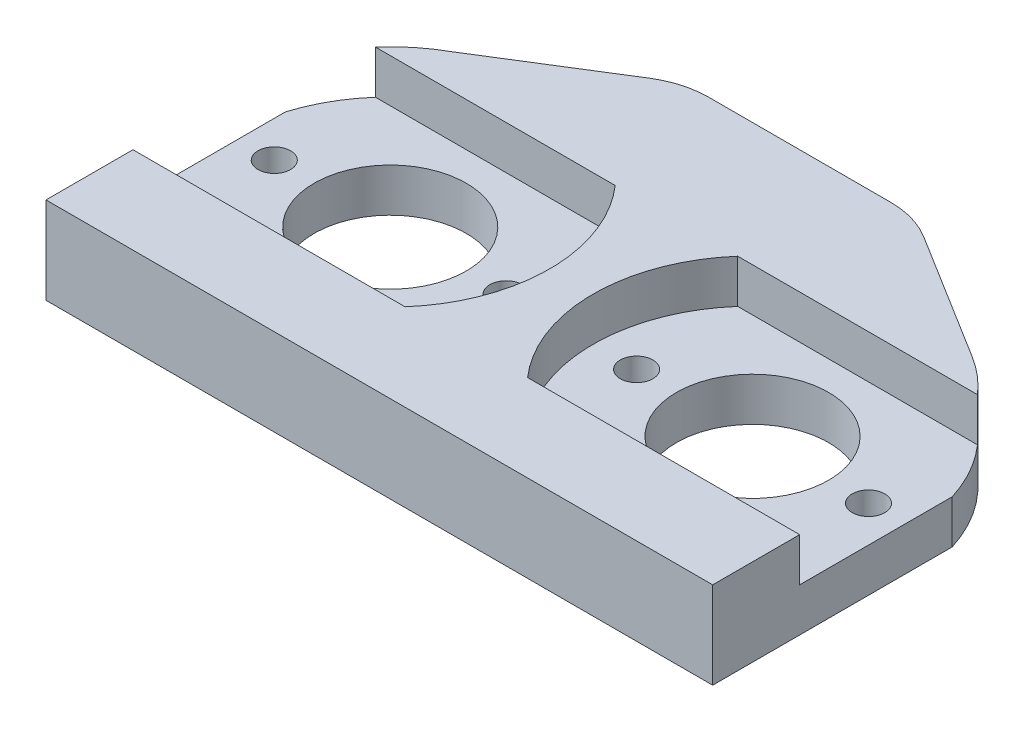
SolidWorks part; units mm, degrees
material "Beech"
ref_plane "Front Plane" through (0, 0, 0) normal (0, 0, 1) x (1, 0, 0)
ref_plane "Top Plane" through (0, 0, 0) normal (0, 1, 0) x (1, 0, 0)
ref_plane "Right Plane" through (0, 0, 0) normal (1, 0, 0) x (0, 0, -1)
sketch "Sketch1" plane through (0, 0, 0) normal (0, 1, 0) x (1, 0, 0)
  line L1 (-46, 28) -> (46, 28)
  line L2 (-46, 28) -> (-46, -28)
  line L3 (-46, -28) -> (46, -28)
  line L4 (46, 28) -> (46, -28)
  line L5 (-46, 28) -> (46, -28) construction
  line L6 (-46, -28) -> (46, 28) construction
  point P0 (0, 0)
  dimension "D1" = 56
  dimension "D2" = 92
extrude "Boss-Extrude1" add sketch "Sketch1" along normal blind 12
sketch "Sketch8" plane through (0, 12, 0) normal (0, 1, 0) x (1, 0, 0)
  line L1 (-46, 28) -> (46, 28)
  line L2 (-46, 28) -> (-46, 30)
  line L3 (-46, 30) -> (46, 30)
  line L4 (46, 28) -> (46, 30)
  dimension "D1" = 2
extrude "Boss-Extrude3" add sketch "Sketch8" against normal blind 12
sketch "Sketch2" plane through (0, 12, 0) normal (0, 1, 0) x (1, 0, 0)
  line L0 (-55.7629, -1.5) -> (57.1831, -1.5) construction
  line L1 (-46, -28) -> (46, -28) construction
  circle A0 centre (-25, -1.5) radius 10.5
  circle A1 centre (25, -1.5) radius 10.5
  point P6 (0, -28)
  dimension "D1" = 21
  dimension "D2" = 21
  dimension "D3" = 50
  dimension "D4" = 25
  dimension "D5" = 26.5
extrude "Cut-Extrude1" cut sketch "Sketch2" against normal up to next
sketch "Sketch5" plane through (0, 12, 0) normal (0, 1, 0) x (1, 0, 0)
  line L0 (-46, 28) -> (-46, -28) construction
  line L1 (46, -28) -> (46, 28) construction
  line L2 (-46, -16) -> (-46, -8.0574)
  line L4 (46, -16) -> (46, -8.0574)
  line L8 (-41.5454, 13) -> (-8.4546, 13)
  line L9 (-8.4546, -16) -> (-46, -16)
  line L10 (8.4546, 13) -> (41.5454, 13)
  line L11 (46, -16) -> (8.4546, -16)
  arc A8 (-8.4546, -16) -> (-8.4546, 13) centre (-25, -1.5) ccw
  arc A9 (-41.5454, 13) -> (-46, -8.0574) centre (-25, -1.5) ccw
  arc A10 (46, -8.0574) -> (41.5454, 13) centre (25, -1.5) ccw
  arc A11 (8.4546, 13) -> (8.4546, -16) centre (25, -1.5) ccw
extrude "Cut-Extrude3" cut sketch "Sketch5" against normal blind 6
sketch "Sketch6" plane through (0, 6, 0) normal (0, 1, 0) x (1, 0, 0)
  circle A0 centre (-41, -1.5) radius 2.25 construction
  circle A1 centre (-9, -1.5) radius 2.25 construction
  circle A2 centre (9, -1.5) radius 2.25 construction
  circle A3 centre (41, -1.5) radius 2.25 construction
  circle A4 centre (-41, -1.5) radius 2.25
  circle A5 centre (-9, -1.5) radius 2.25
  circle A6 centre (9, -1.5) radius 2.25
  circle A7 centre (41, -1.5) radius 2.25
extrude "Cut-Extrude4" cut sketch "Sketch6" against normal up to next
sketch "Sketch10" plane through (0, 12, 0) normal (0, 1, 0) x (1, 0, 0)
  line L0 (-46, 5.0574) -> (-46, 30)
  line L1 (46, 30) -> (-46, 30) construction
  line L2 (-46, 30) -> (-16, 30)
  line L4 (-16, 30) -> (-35.6673, 17.7408)
  line L5 (46, 5.0574) -> (46, 30)
  line L6 (46, 30) -> (16, 30)
  line L8 (16, 30) -> (36.6154, 17.1838)
  arc A0 (-41.5454, 13) -> (-46, 5.0574) centre (-25, -1.5) ccw construction
  arc A1 (46, 5.0574) -> (41.5454, 13) centre (25, -1.5) ccw construction
  arc A2 (-35.6673, 17.7408) -> (-46, 5.0574) centre (-25, -1.5) ccw
  arc A3 (46, 5.0574) -> (36.6154, 17.1838) centre (25, -1.5) ccw
  dimension "D1" = 30
  dimension "D2" = 30
extrude "Cut-Extrude5" cut sketch "Sketch10" against normal up to next
fillet "Fillet2" radius 12 2 edges at (16, 6, -30) (-16, 6, -30)
